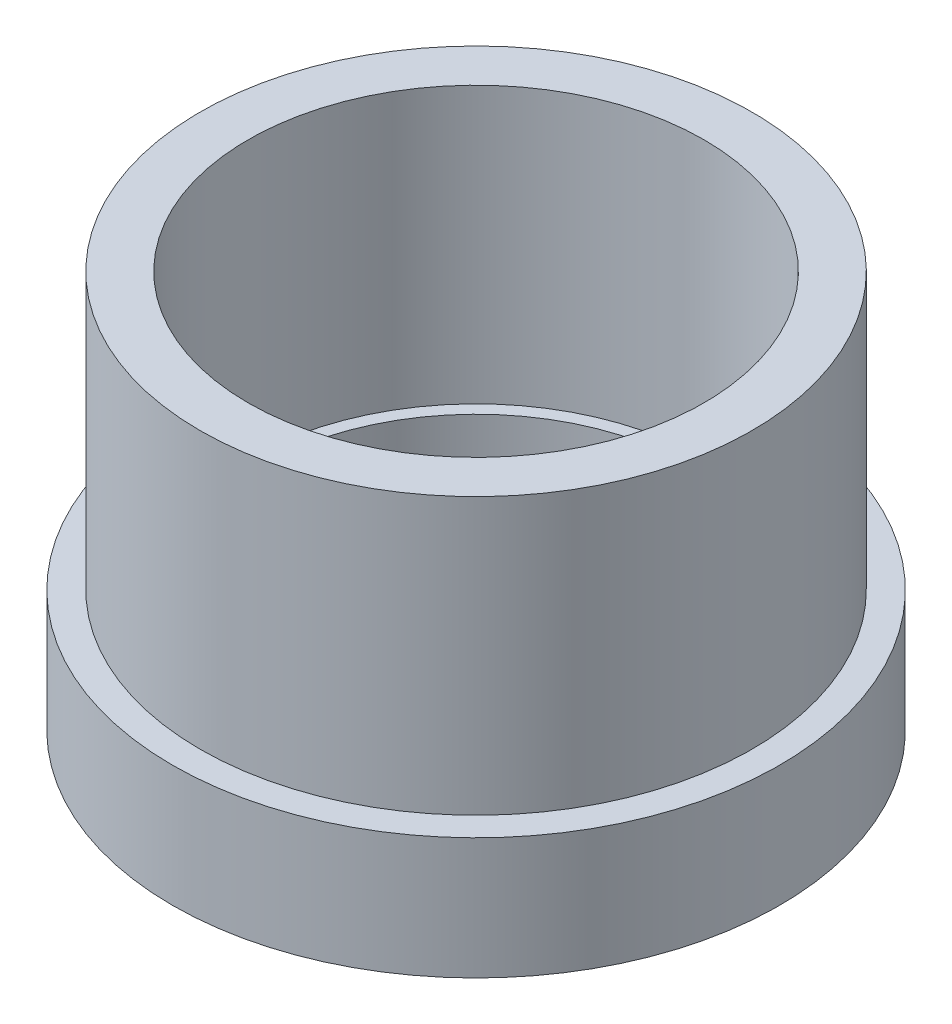
SolidWorks part; units mm, degrees
material "Custom Plastic"
ref_plane "Front Plane" through (0, 0, 0) normal (0, 0, 1) x (1, 0, 0)
ref_plane "Top Plane" through (0, 0, 0) normal (0, 1, 0) x (1, 0, 0)
ref_plane "Right Plane" through (0, 0, 0) normal (1, 0, 0) x (0, 0, -1)
sketch "Sketch1" plane through (0, 0, 0) normal (0, 0, 1) x (1, 0, 0)
  line L0 (39, 0) -> (39, 10)
  line L1 (0, 83.5208) -> (0, -98.2024) construction
  line L2 (39, 10) -> (55, 10)
  line L3 (55, 10) -> (55, -12)
  line L4 (55, -12) -> (41.5, -12)
  line L5 (41.5, -12) -> (41.5, 0)
  line L6 (41.5, 0) -> (39, 0)
  dimension "D1" = 39
  dimension "D2" = 55
  dimension "D3" = 41.5
  dimension "D4" = 22
  dimension "D5" = 10
  dimension "D6" = 0
revolve "Revolve1" add sketch "Sketch1" angle 360 about L1
sketch "Sketch3" plane through (0, -12, 0) normal (0, -1, 0) x (1, 0, 0)
  circle A0 centre (0, 48.25) radius 1.6
  circle A4 centre (48.25, 0) radius 1.6
  circle A5 centre (0, -48.25) radius 1.6
  circle A6 centre (-48.25, 0) radius 1.6
  point P12 (0, 0)
  point P13 (0, 0)
  dimension "D1" = 3.2
  dimension "D2" = 48.25
  dimension "D3" = 4
sketch "Sketch4" plane through (0, 10, 0) normal (0, 1, 0) x (1, 0, 0)
  circle A0 centre (0, 0) radius 41.3
  circle A1 centre (0, 0) radius 50
  dimension "D1" = 82.6
  dimension "D2" = 100
extrude "Boss-Extrude1" add sketch "Sketch4" along normal blind 50
extrude "Cut-Extrude1" cut sketch "Sketch3" against normal blind 10 contours A0 | A6 | A5 | A4
